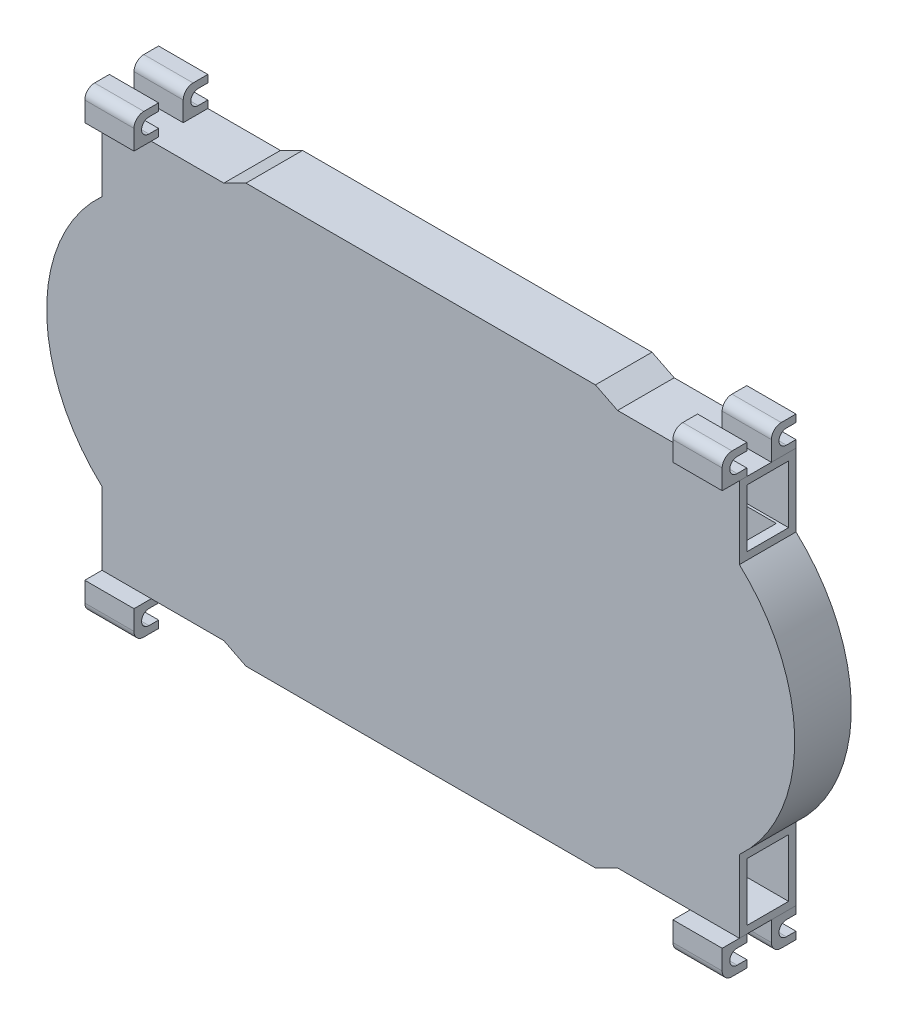
SolidWorks part; units mm, degrees
ref_plane "前视基准面" through (0, 0, 0) normal (0, 0, 1) x (1, 0, 0)
ref_plane "上视基准面" through (0, 0, 0) normal (0, 1, 0) x (1, 0, 0)
ref_plane "右视基准面" through (0, 0, 0) normal (1, 0, 0) x (0, 0, -1)
sketch "草图1" plane through (0, 0, 0) normal (0, 0, 1) x (1, 0, 0)
  line L0 (0, 72.4752) -> (0, -78.8585) construction
  line L1 (-76, 42.5) -> (76, 42.5)
  line L2 (-76, 42.5) -> (-76, -42.5)
  line L3 (-76, -42.5) -> (76, -42.5)
  line L4 (76, 42.5) -> (76, -42.5)
  line L5 (-109.7664, 0) -> (128.4587, 0) construction
  dimension "D1" = 152
  dimension "D2" = 85
extrude "凸台-拉伸1" add sketch "草图1" along normal blind 10
sketch "草图2" plane through (0, 0, 10) normal (0, 0, 1) x (1, 0, 0)
  line L0 (0, 55.2134) -> (0, -56.7825) construction
  line L1 (-93.0684, 0) -> (90.1263, 0) construction
  line L2 (-35.5, 42.5) -> (-40, 40.25)
  line L4 (76, 42.5) -> (-76, 42.5) construction
  line L5 (-40, 40.25) -> (-76, 40.25)
  line L7 (-76, 42.5) -> (-76, -42.5) construction
  line L8 (-76, 40.25) -> (-76, 42.5)
  line L9 (-76, 42.5) -> (-35.5, 42.5)
  line L10 (76, 42.5) -> (35.5, 42.5)
  line L11 (76, 40.25) -> (76, 42.5)
  line L12 (40, 40.25) -> (76, 40.25)
  line L13 (35.5, 42.5) -> (40, 40.25)
  line L14 (35.5, -42.5) -> (40, -40.25)
  line L15 (40, -40.25) -> (76, -40.25)
  line L16 (76, -40.25) -> (76, -42.5)
  line L17 (76, -42.5) -> (35.5, -42.5)
  line L18 (-76, -42.5) -> (-35.5, -42.5)
  line L19 (-76, -40.25) -> (-76, -42.5)
  line L20 (-40, -40.25) -> (-76, -40.25)
  line L21 (-35.5, -42.5) -> (-40, -40.25)
  dimension "D1" = 71
  dimension "D2" = 80.5
  dimension "D3" = 36
extrude "切除-拉伸1" cut sketch "草图2" against normal through all
sketch "草图3" plane through (0, 0, 10) normal (0, 0, 1) x (1, 0, 0)
  line L0 (-113.5829, 0) -> (96.2926, 0) construction
  line L1 (0, 67.6043) -> (0, -58.321) construction
  line L2 (-64.75, -25.5) -> (-64.75, -40.25)
  line L3 (-40, -40.25) -> (-76, -40.25) construction
  line L4 (-76, 40.25) -> (-76, -40.25) construction
  line L5 (-76, -40.25) -> (-76, 40.25)
  line L6 (-64.75, -40.25) -> (-76, -40.25)
  line L7 (64.75, 40.25) -> (76, 40.25)
  line L8 (64.75, 25.5) -> (64.75, 40.25)
  line L9 (64.75, -40.25) -> (76, -40.25)
  line L10 (-64.75, 25.5) -> (-64.75, 40.25)
  line L11 (-76, 40.25) -> (-40, 40.25) construction
  line L12 (-64.75, 40.25) -> (-76, 40.25)
  line L13 (76, -40.25) -> (76, 40.25)
  line L14 (64.75, -25.5) -> (64.75, -40.25)
  arc A0 (-64.75, 25.5) -> (-64.75, -25.5) centre (-41.4443, 0) ccw
  arc A1 (64.75, 25.5) -> (64.75, -25.5) centre (41.4443, 0) cw
  point P15 (-76, 0)
  point P17 (76, 0)
  dimension "D1" = 51
  dimension "D2" = 129.5
extrude "切除-拉伸2" cut sketch "草图3" against normal through all
shell "抽壳1" thickness 2
sketch "草图7" plane through (0, 0, 10) normal (0, 0, 1) x (1, 0, 0)
  line L0 (-64.75, 40.25) -> (-40, 40.25) construction
  line L1 (-40, 40.25) -> (-35.5, 42.5) construction
  line L2 (35.5, 42.5) -> (-35.5, 42.5) construction
  line L3 (35.5, 42.5) -> (40, 40.25) construction
  line L4 (40, 40.25) -> (64.75, 40.25) construction
  line L5 (64.75, 40.25) -> (64.75, 25.5) construction
  line L6 (64.75, -25.5) -> (64.75, -40.25) construction
  line L8 (40, -40.25) -> (35.5, -42.5) construction
  line L9 (-35.5, -42.5) -> (35.5, -42.5) construction
  line L10 (-35.5, -42.5) -> (-40, -40.25) construction
  line L11 (-40, -40.25) -> (-64.75, -40.25) construction
  line L12 (-64.75, -40.25) -> (-64.75, -25.5) construction
  line L13 (-64.75, 25.5) -> (-64.75, 40.25) construction
  line L14 (-64.75, 40.25) -> (-40, 40.25)
  line L15 (-40, 40.25) -> (-35.5, 42.5)
  line L16 (35.5, 42.5) -> (-35.5, 42.5)
  line L17 (35.5, 42.5) -> (40, 40.25)
  line L18 (40, 40.25) -> (64.75, 40.25)
  line L19 (64.75, 40.25) -> (64.75, 25.5)
  line L20 (64.75, -25.5) -> (64.75, -40.25)
  line L21 (64.75, -40.25) -> (40, -40.25) construction
  line L22 (40, -40.25) -> (35.5, -42.5)
  line L23 (-35.5, -42.5) -> (35.5, -42.5)
  line L24 (-35.5, -42.5) -> (-40, -40.25)
  line L25 (-40, -40.25) -> (-64.75, -40.25)
  line L26 (-64.75, -40.25) -> (-64.75, -25.5)
  line L27 (-64.75, 25.5) -> (-64.75, 40.25)
  line L28 (64.75, -40.25) -> (40, -40.25)
  arc A0 (64.75, -25.5) -> (64.75, 25.5) centre (41.4443, 0) ccw construction
  arc A1 (-64.75, 25.5) -> (-64.75, -25.5) centre (-41.4443, 0) ccw construction
  arc A2 (64.75, -25.5) -> (64.75, 25.5) centre (41.4443, 0) ccw
  arc A3 (-64.75, 25.5) -> (-64.75, -25.5) centre (-41.4443, 0) ccw
extrude "凸台-拉伸3" add sketch "草图7" along normal blind 1.5
sketch "草图5" plane through (64.75, 0, 0) normal (1, 0, 0) x (0, 0, -1)
  line L0 (0, 40.25) -> (-11.5, 40.25) construction
  line L1 (0, 42.5) -> (0, 40.25) construction
  line L2 (0, 40.25) -> (-5, 40.25)
  line L3 (-5, 40.25) -> (-5, 44.25)
  line L4 (-3, 46.25) -> (0, 46.25)
  line L5 (0, 46.25) -> (0, 44.75)
  line L6 (0, 44.75) -> (-1.9603, 44.75)
  line L7 (3.4171, 43.25) -> (-9.5732, 43.25) construction
  line L8 (-1.9603, 41.75) -> (0, 41.75)
  line L9 (0, 41.75) -> (0, 40.25)
  line L10 (0, 40.25) -> (0, 25.5) construction
  line L11 (-10, 40.25) -> (-15, 40.25)
  line L12 (-15, 40.25) -> (-15, 44.25)
  line L13 (-13, 46.25) -> (-10, 46.25)
  line L14 (-10, 46.25) -> (-10, 44.75)
  line L15 (-10, 44.75) -> (-11.9603, 44.75)
  line L16 (-11.9603, 41.75) -> (-10, 41.75)
  line L17 (-10, 41.75) -> (-10, 40.25)
  line L18 (36.476, 0) -> (-41.4655, 0) construction
  line L19 (3.4171, -43.25) -> (-9.5732, -43.25) construction
  line L20 (-10, -41.75) -> (-10, -40.25)
  line L21 (-11.9603, -41.75) -> (-10, -41.75)
  line L22 (-10, -44.75) -> (-11.9603, -44.75)
  line L23 (-10, -46.25) -> (-10, -44.75)
  line L24 (-13, -46.25) -> (-10, -46.25)
  line L25 (-15, -40.25) -> (-15, -44.25)
  line L26 (-10, -40.25) -> (-15, -40.25)
  line L27 (0, -41.75) -> (0, -40.25)
  line L28 (-1.9603, -41.75) -> (0, -41.75)
  line L29 (0, -44.75) -> (-1.9603, -44.75)
  line L30 (0, -46.25) -> (0, -44.75)
  line L31 (-3, -46.25) -> (0, -46.25)
  line L32 (-5, -40.25) -> (-5, -44.25)
  line L33 (0, -40.25) -> (-5, -40.25)
  arc A0 (-3, 46.25) -> (-5, 44.25) centre (-3, 44.25) ccw
  arc A1 (-1.9603, 44.75) -> (-1.9603, 41.75) centre (-1.9603, 43.25) ccw
  arc A2 (-13, 46.25) -> (-15, 44.25) centre (-13, 44.25) ccw
  arc A3 (-11.9603, 44.75) -> (-11.9603, 41.75) centre (-11.9603, 43.25) ccw
  arc A4 (-11.9603, -44.75) -> (-11.9603, -41.75) centre (-11.9603, -43.25) cw
  arc A5 (-13, -46.25) -> (-15, -44.25) centre (-13, -44.25) cw
  arc A6 (-1.9603, -44.75) -> (-1.9603, -41.75) centre (-1.9603, -43.25) cw
  arc A7 (-3, -46.25) -> (-5, -44.25) centre (-3, -44.25) cw
  point P18 (-5, 46.25)
  point P58 (-5, -46.25)
  dimension "D5" = 2
  dimension "D6" = 1.5
  dimension "D1" = 5
  dimension "D2" = 6
  dimension "D3" = 1.5
  dimension "D4" = 1.5
  dimension "D7" = 2
extrude "凸台-拉伸2" add sketch "草图5" against normal blind 10 separate body
mirror "镜向10" about plane through (0, 0, 0) normal (1, 0, 0) of "凸台-拉伸2"
sketch "草图6" plane through (64.75, 0, 0) normal (1, 0, 0) x (0, 0, -1)
  line L0 (19.8396, 0) -> (-22.9539, 0) construction
  line L8 (-1.5, -38.75) -> (-10, -38.75)
  line L9 (-10, -27) -> (-1.5, -27)
  line L10 (-1.5, -27) -> (-1.5, -38.75)
  line L11 (-10, -38.75) -> (-10, -27)
  line L29 (-10, 38.75) -> (-10, 27)
  line L30 (-1.5, 27) -> (-1.5, 38.75)
  line L31 (-10, 27) -> (-1.5, 27)
  line L32 (-1.5, 38.75) -> (-10, 38.75)
  line L33 (-10, 38.75) -> (-10, 27)
  line L34 (-1.5, 27) -> (-1.5, 38.75)
  line L35 (-10, 27) -> (-1.5, 27)
  line L36 (-1.5, 38.75) -> (-10, 38.75)
  dimension "D1" = 1.5
extrude "切除-拉伸4" cut sketch "草图6" against normal through all
sketch "草图4" plane through (0, 0, 0) normal (0, 0, -1) x (-1, 0, 0)
  line L0 (-96.4027, 0) -> (94.6375, 0) construction
  line L1 (0, 51.8153) -> (0, -53.8033) construction
  circle A0 centre (-45, 0) radius 2.5
  circle A4 centre (45, 0) radius 2.5
  dimension "D1" = 5
extrude "切除-拉伸3" cut sketch "草图4" against normal blind 3
